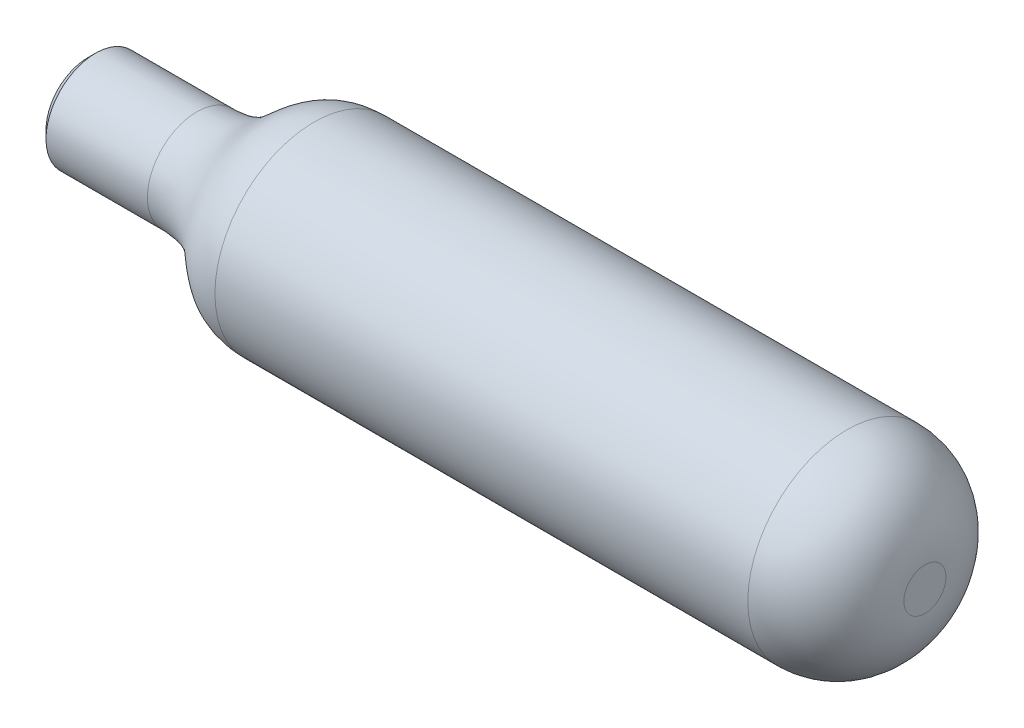
SolidWorks part; units mm, degrees
ref_plane "Front Plane" through (0, 0, 0) normal (0, 0, 1) x (1, 0, 0)
ref_plane "Top Plane" through (0, 0, 0) normal (0, 1, 0) x (1, 0, 0)
ref_plane "Right Plane" through (0, 0, 0) normal (1, 0, 0) x (0, 0, -1)
sketch "revolution body" plane through (0, 0, 0) normal (0, 0, 1) x (1, 0, 0)
  line L0 (-67.0343, 8.8194) -> (-54.0343, 8.8194)
  line L1 (-39.0343, 15.1694) -> (29.2657, 15.1694)
  line L2 (-68.0343, 7.8194) -> (-67.0343, 8.8194)
  line L3 (-68.0343, 2.4694) -> (39.2657, 2.4694)
  line L4 (39.2657, 5.1694) -> (39.2657, 2.4694)
  line L10 (-68.0343, 2.4694) -> (-68.0343, 7.8194)
  arc A0 (29.2657, 15.1694) -> (39.2657, 5.1694) centre (29.2657, 5.1694) cw
  spline S0 degree 3 poles (-54.0343, 8.8194) (-45.6399, 8.7161) (-46.4251, 15.0317) (-39.0343, 15.1694) knots 0 0 0 0 1 1 1 1
  point P7 (0, 0)
  point P9 (-68.0343, 8.8194)
  dimension "D3" = 10
  dimension "D1" = 107.3
  dimension "D2" = 14
  dimension "D4" = 6.35
  dimension "D5" = 12.7
  dimension "D6" = 15
revolve "Revolve1" add sketch "revolution body" angle 360 about L3
